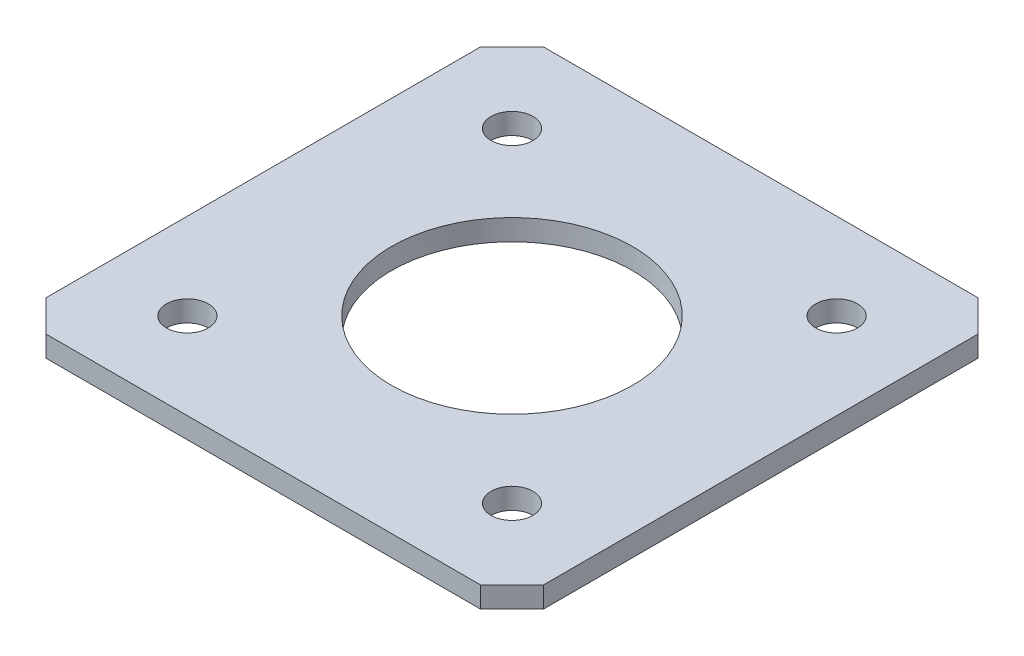
SolidWorks part; units mm, degrees
ref_plane "Front Plane" through (0, 0, 0) normal (0, 0, 1) x (1, 0, 0)
ref_plane "Top Plane" through (0, 0, 0) normal (0, 1, 0) x (1, 0, 0)
ref_plane "Right Plane" through (0, 0, 0) normal (1, 0, 0) x (0, 0, -1)
sketch "Sketch2" plane through (0, 0, 0) normal (0, 1, 0) x (1, 0, 0)
  line L1 (-15.5, -15.5) -> (15.5, -15.5) construction
  line L2 (-15.5, -15.5) -> (-15.5, 15.5) construction
  line L3 (-15.5, 15.5) -> (15.5, 15.5) construction
  line L4 (15.5, -15.5) -> (15.5, 15.5) construction
  line L5 (-15.5, -15.5) -> (15.5, 15.5) construction
  line L6 (-15.5, 15.5) -> (15.5, -15.5) construction
  line L7 (-23.75, -23.75) -> (23.75, -23.75)
  line L8 (-23.75, -23.75) -> (-23.75, 23.75)
  line L9 (-23.75, 23.75) -> (23.75, 23.75)
  line L10 (23.75, -23.75) -> (23.75, 23.75)
  line L11 (-23.75, -23.75) -> (23.75, 23.75) construction
  line L12 (-23.75, 23.75) -> (23.75, -23.75) construction
  circle A0 centre (-15.5, 15.5) radius 2
  circle A1 centre (15.5, 15.5) radius 2
  circle A2 centre (15.5, -15.5) radius 2
  circle A3 centre (-15.5, -15.5) radius 2
  circle A4 centre (0, 0) radius 11.5
  point P0 (0, 0)
  point P6 (0, 0)
  point P21 (0, 0)
  dimension "D5" = 4
  dimension "D7" = 23
  dimension "D1" = 31
  dimension "D2" = 47.5
  dimension "D3" = 47.5
  dimension "D4" = 31
  dimension "D6" = 4
extrude "Boss-Extrude1" add sketch "Sketch2" along normal blind 2
chamfer "Chamfer1" distance 3 angle 45 4 edges at (23.75, 1, -23.75) (-23.75, 1, -23.75) (-23.75, 1, 23.75) (23.75, 1, 23.75)
